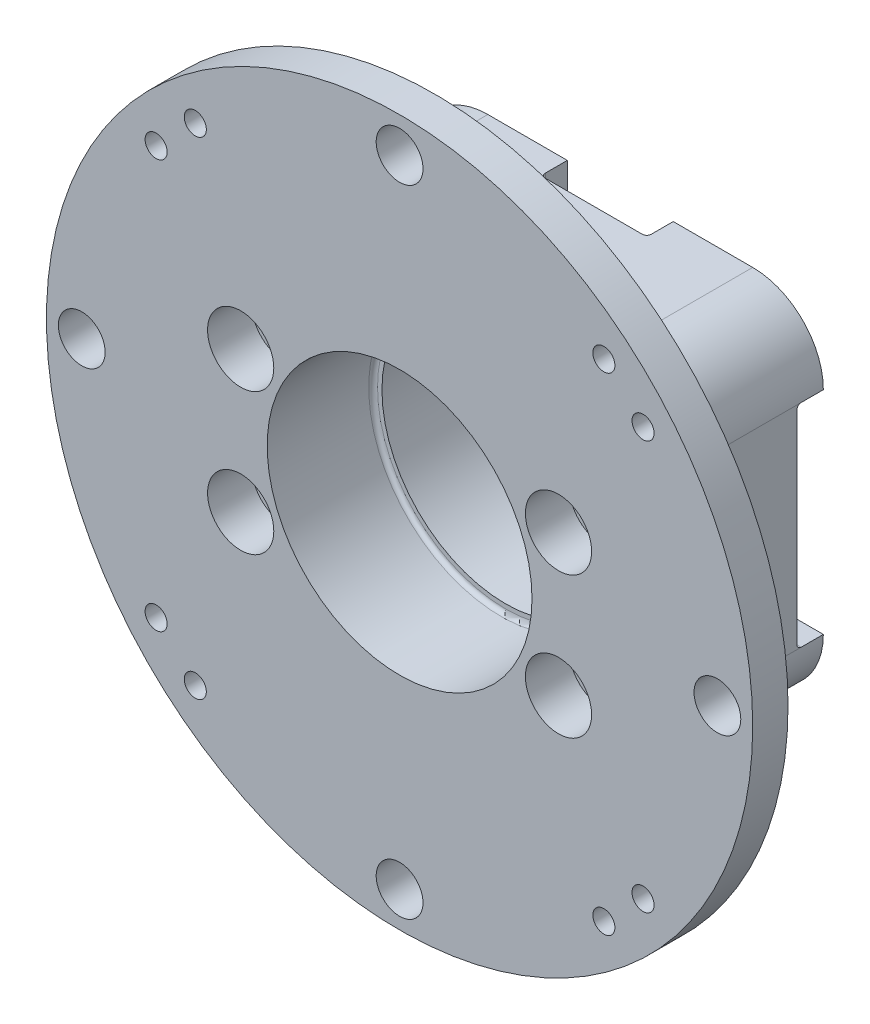
SolidWorks part; units mm, degrees
material "6061 Alloy"
ref_plane "Front Plane" through (0, 0, 0) normal (0, 0, 1) x (1, 0, 0)
ref_plane "Top Plane" through (0, 0, 0) normal (0, 1, 0) x (1, 0, 0)
ref_plane "Right Plane" through (0, 0, 0) normal (1, 0, 0) x (0, 0, -1)
sketch "Sketch1" plane through (0, 0, 0) normal (0, 0, 1) x (1, 0, 0)
  line L1 (-23, -20) -> (23, -20)
  line L2 (-23, -20) -> (-23, 20)
  line L3 (-23, 20) -> (23, 20)
  line L4 (23, -20) -> (23, 20)
  dimension "D1" = 46
  dimension "D2" = 40
  dimension "D3" = 23
  dimension "D4" = 20
extrude "Boss-Extrude1" add sketch "Sketch1" along normal blind 21
sketch "Sketch2" plane through (0, 0, 0) normal (0, 0, -1) x (-1, 0, 0)
  line L0 (-12.7377, 12) -> (-23, 12)
  line L1 (-23, -20) -> (-23, 20) construction
  line L2 (23, 12) -> (12.7377, 12)
  line L3 (23, 20) -> (23, -20) construction
  line L4 (-23, -12) -> (-12.7377, -12)
  line L5 (23, -12) -> (12.7377, -12)
  line L6 (6, 20) -> (6, 16.4393)
  line L7 (-23, 20) -> (23, 20) construction
  line L8 (6, -20) -> (6, -16.4393)
  line L9 (23, -20) -> (-23, -20) construction
  line L10 (-6, 20) -> (-6, 16.4393)
  line L11 (-6, -20) -> (-6, -16.4393)
  line L12 (6, 20) -> (-6, 20)
  line L13 (6, -20) -> (-6, -20)
  circle A0 centre (0, 0) radius 17.5
  line M1 (23, -20) -> (23, 20)
  line M2 (23, 20) -> (-23, 20)
  line M3 (-23, 20) -> (-23, -20)
  line M4 (-23, -20) -> (23, -20)
  dimension "D1" = 35
  dimension "D2" = 24
  dimension "D3" = 12
  dimension "D4" = 6
  dimension "D5" = 6
extrude "Cut-Extrude1" cut sketch "Sketch2" against normal blind 3 contours A0 L6 L10 M2 | A0 L5 L2 M1 | A0 L11 L8 M4 | A0 L0 L4 M3 | A0 L0
fillet "Fillet1" radius 8 4 edges at (-23, -20, 10.5) (23, -20, 10.5) (-23, 20, 10.5) (23, 20, 10.5)
sketch "Sketch20" plane through (0, 0, 21) normal (0, 0, 1) x (1, 0, 0)
  circle A0 centre (0, 0) radius 40
  dimension "D1" = 80
extrude "Boss-Extrude3" add sketch "Sketch20" along normal blind 4
hole_wizard "M5 Clearance Hole2" positions "Sketch22" profile "Sketch23" hole size "M5" standard "ANSI Metric" end condition through all
sketch "Sketch22" plane through (0, 0, 25) normal (0, 0, 1) x (1, 0, 0)
  line L0 (0, 0) -> (-36, 0) construction
  circle A0 centre (0, 0) radius 36 construction
  point P0 (-36, 0)
sketch "Sketch23" plane through (-36, 0, 25) normal (1, 0, 0) x (0, -1, 0)
  line L0 (0, 0) -> (0, 25)
  line L1 (0, 25) -> (2.65, 25)
  line L2 (2.65, 25) -> (2.65, 0)
  line L5 (2.65, 0) -> (0, 0)
  line L11 (0, -6.35) -> (0, 107.95) construction
  dimension "Thru Hole Dia." = 5.3
  dimension "Thru Hole Depth" = 25
pattern_circular "CirPattern3" count 4 over 360 about axis through (0, 0, 0) along (0, 0, 1) of "M5 Clearance Hole2"
sketch "Sketch24" plane through (0, 0, 3) normal (0, 0, -1) x (-1, 0, 0)
  circle A0 centre (0, 0) radius 14
  dimension "D1" = 28
extrude "Cut-Extrude2" cut sketch "Sketch24" against normal through all
sketch "Sketch25" plane through (0, 0, 25) normal (0, 0, 1) x (1, 0, 0)
  circle A0 centre (0, 0) radius 15
  dimension "D1" = 30
extrude "Cut-Extrude3" cut sketch "Sketch25" against normal blind 12
hole_wizard "M3x0.5 Tapped Hole1" positions "Sketch27" profile "Sketch28" tap size "M3x0.5" standard "ANSI Metric" end condition through all
sketch "Sketch27" plane through (0, 0, 21) normal (0, 0, -1) x (-1, 0, 0)
  line L0 (0, 0) -> (37.815, 37.815) construction
  line L2 (0, 0) -> (0, 36) construction
  line L4 (0, 0) -> (36, 0) construction
  line L11 (0, 0) -> (27.5776, 23.1404) construction
  line L13 (0, 0) -> (23.1404, 27.5776) construction
  circle A0 centre (0, 0) radius 36 construction
  point P0 (23.1404, 27.5776)
  point P2 (27.5776, 23.1404)
  dimension "D1" = 45
  dimension "D2" = 5
  dimension "D3" = 5
sketch "Sketch28" plane through (-23.1404, 27.5776, 21) normal (1, 0, 0) x (0, 1, 0)
  line L0 (0, 0) -> (0, 4)
  line L1 (0, 4) -> (1.25, 4)
  line L2 (1.25, 4) -> (1.25, 0)
  line L5 (1.25, 0) -> (0, 0)
  line L11 (0, -6.35) -> (0, 107.95) construction
  dimension "Thru Tap Drill Dia." = 2.5
  dimension "Thru Tap Drill Depth" = 4
cosmetic thread "Hole Thread1" parameters "D2"=3
cosmetic thread "Hole Thread2" parameters "D2"=3
pattern_circular "CirPattern4" count 4 every 90 about axis through (0, 0, 0) along (0, 0, 1) of "M3x0.5 Tapped Hole1"
cosmetic thread "Hole Thread3" parameters "D2"=3
cosmetic thread "Hole Thread4" parameters "D2"=3
cosmetic thread "Hole Thread5" parameters "D2"=3
cosmetic thread "Hole Thread6" parameters "D2"=3
cosmetic thread "Hole Thread7" parameters "D2"=3
cosmetic thread "Hole Thread8" parameters "D2"=3
hole_wizard "CBORE for M4 SBHCS1" positions "Sketch29" profile "Sketch30" counterbore size "M4" standard "ANSI Metric" end condition through all
sketch "Sketch29" plane through (0, 0, 25) normal (0, 0, 1) x (1, 0, 0)
  line L1 (-18, -8) -> (18, -8) construction
  line L2 (-18, -8) -> (-18, 8) construction
  line L3 (-18, 8) -> (18, 8) construction
  line L4 (18, -8) -> (18, 8) construction
  point P0 (-18, -8)
  point P2 (-18, 8)
  point P4 (18, -8)
  point P6 (18, 8)
  dimension "D1" = 16
  dimension "D2" = 8
  dimension "D3" = 36
  dimension "D4" = 18
sketch "Sketch30" plane through (-18, -8, 25) normal (1, 0, 0) x (0, -1, 0)
  line L0 (0, 0) -> (0, 25)
  line L1 (0, 25) -> (2.15, 25)
  line L3 (2.15, 25) -> (2.15, 5)
  line L4 (2.15, 5) -> (3.75, 5)
  line L5 (3.75, 5) -> (3.75, 0)
  line L7 (3.75, 0) -> (0, 0)
  line L11 (0, -6.35) -> (0, 107.95) construction
  dimension "Thru Hole Dia." = 4.3
  dimension "Thru Hole Depth" = 25
  dimension "C'Bore Dia." = 7.5
  dimension "C'Bore Depth" = 5
fillet "Fillet2" radius 1 8 edges at (20.6569, -17.6569, 21) (20.6569, 17.6569, 21) (23, 0, 21) (0, -20, 21) (-20.6569, -17.6569, 21) (-23, 0, 21) (-20.6569, 17.6569, 21) (0, 20, 21)
fillet "Fillet3" radius 0.5 12 edges at (6, 18.2196, 3) (9.6282, 14.6133, 3) (17.8689, 12, 3) (17.8689, -12, 3) (9.6282, -14.6133, 3) (6, -18.2196, 3) (-6, -18.2196, 3) (-9.6282, -14.6133, 3) (-17.8689, -12, 3) (-6, 18.2196, 3) (-9.6282, 14.6133, 3) (-17.8689, 12, 3)
fillet "Fillet4" radius 0.5 1 edges at (15, 0, 13)
